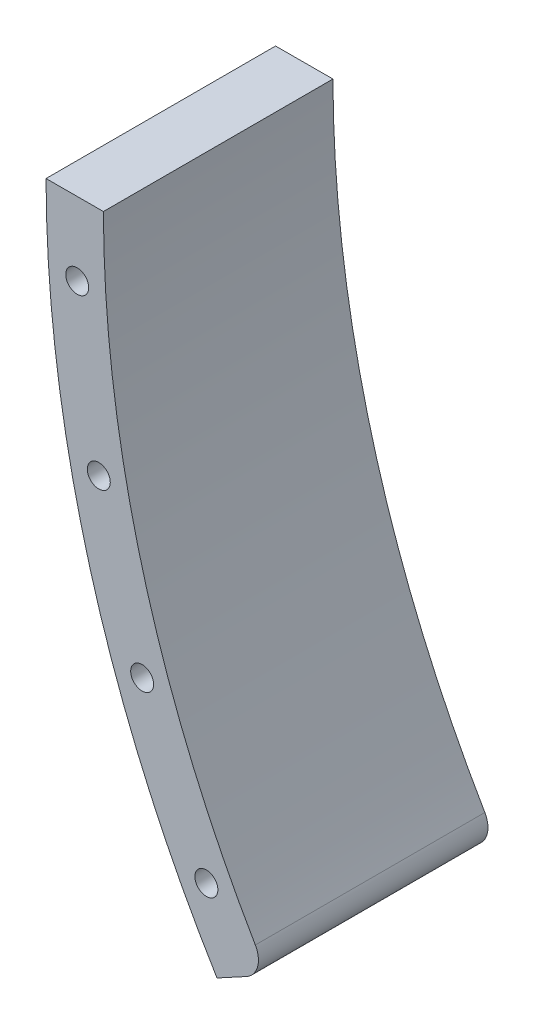
SolidWorks part; units mm, degrees
ref_plane "Front Plane" through (0, 0, 0) normal (0, 0, 1) x (1, 0, 0)
ref_plane "Top Plane" through (0, 0, 0) normal (0, 1, 0) x (1, 0, 0)
ref_plane "Right Plane" through (0, 0, 0) normal (1, 0, 0) x (0, 0, -1)
sketch "Sketch1" plane through (0, 0, 0) normal (0, 0, 1) x (1, 0, 0)
  line L2 (-123.9997, -12.7366) -> (-133.9996, -12.7556)
  line L3 (-95.4065, -113.7422) -> (-104.2053, -118.5215)
  arc A9 (-133.9996, -12.7556) -> (-104.2053, -118.5215) centre (70, -12.3683) ccw construction
  circle A10 centre (-128.5655, -25.5108) radius 2
  circle A11 centre (-124.804, -53.0179) radius 2
  circle A12 centre (-117.2509, -79.7337) radius 2
  circle A13 centre (-106.0531, -105.1384) radius 2
  arc A14 (-123.9997, -12.7366) -> (-95.4065, -113.7422) centre (70, -12.3683) ccw
  arc A15 (-133.9996, -12.7556) -> (-104.2053, -118.5215) centre (70, -12.3683) ccw
  dimension "D1" = 4
  dimension "D2" = 4
  dimension "D3" = 4
  dimension "D4" = 4
extrude "Boss-Extrude1" add sketch "Sketch1" along normal blind 40
fillet "Fillet1" radius 4 1 edges at (-95.4065, -113.7422, 20)
